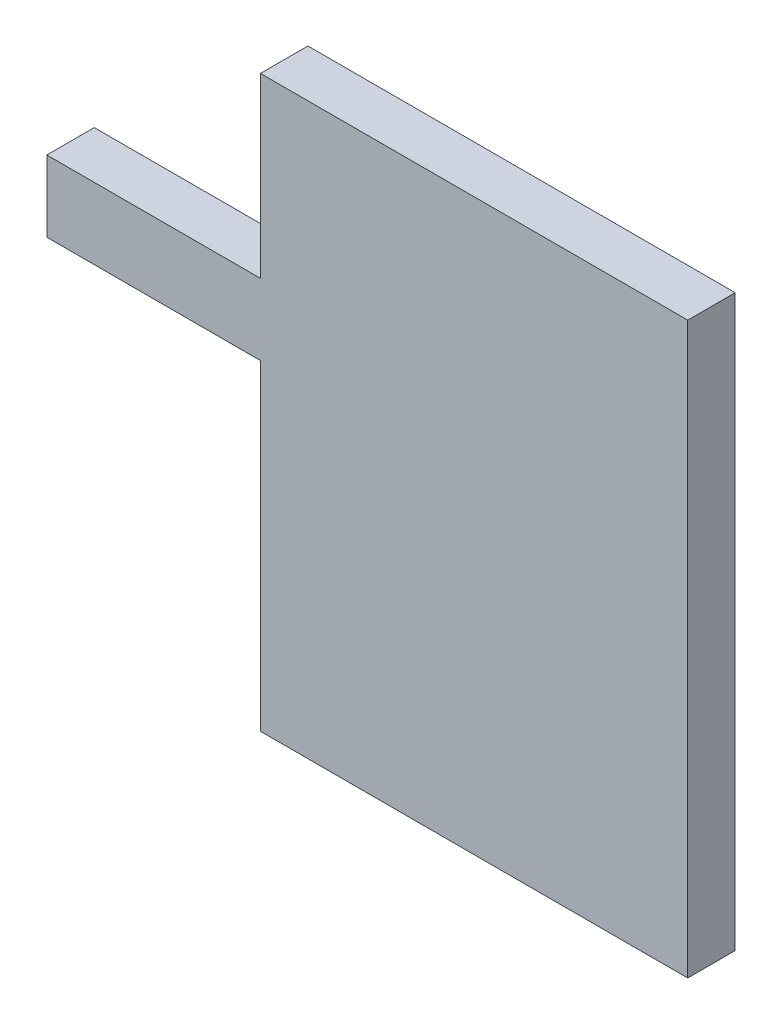
SolidWorks part; units mm, degrees
ref_plane "Front Plane" through (0, 0, 0) normal (0, 0, 1) x (1, 0, 0)
ref_plane "Top Plane" through (0, 0, 0) normal (0, 1, 0) x (1, 0, 0)
ref_plane "Right Plane" through (0, 0, 0) normal (1, 0, 0) x (0, 0, -1)
sketch "Sketch1" plane through (0, 0, 0) normal (0, 0, 1) x (1, 0, 0)
  line L0 (32.6534, 14.8407) -> (-57.3466, 14.8407) construction
  line L1 (-57.3466, 74.8407) -> (32.6534, 74.8407)
  line L2 (-57.3466, 74.8407) -> (-57.3466, 37.4607)
  line L3 (-57.3466, -45.1593) -> (32.6534, -45.1593)
  line L4 (32.6534, 74.8407) -> (32.6534, -45.1593)
  line L5 (-102.3466, 37.4607) -> (-57.3466, 37.4607)
  line L6 (-102.3466, 37.4607) -> (-102.3466, 22.4607)
  line L7 (-102.3466, 22.4607) -> (-57.3466, 22.4607)
  line L9 (-57.3466, 22.4607) -> (-57.3466, -45.1593)
  point P10 (-102.3466, 29.9607)
  dimension "D1" = 120
  dimension "D2" = 90
  dimension "D3" = 15.12
  dimension "D4" = 15
  dimension "D5" = 45
extrude "Boss-Extrude1" add sketch "Sketch1" along normal blind 10
